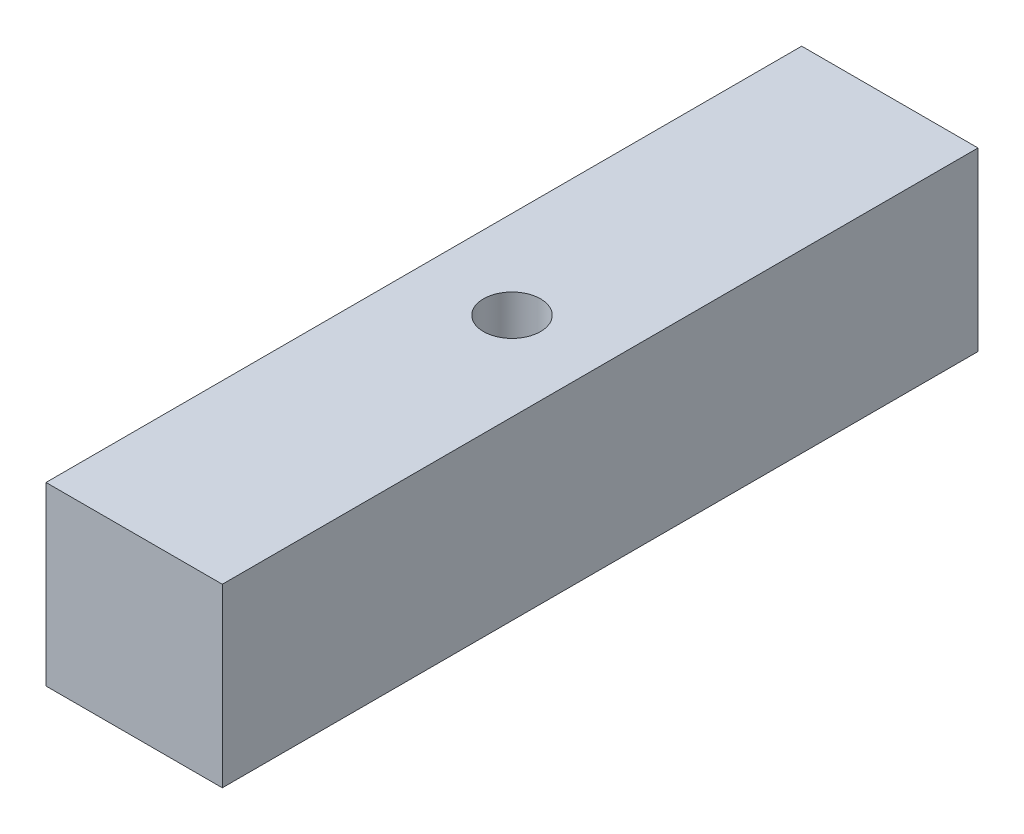
SolidWorks part; units mm, degrees
ref_plane "Front Plane" through (0, 0, 0) normal (0, 0, 1) x (1, 0, 0)
ref_plane "Top Plane" through (0, 0, 0) normal (0, 1, 0) x (1, 0, 0)
ref_plane "Right Plane" through (0, 0, 0) normal (1, 0, 0) x (0, 0, -1)
sketch "Sketch1" plane through (0, 0, 0) normal (0, 0, 1) x (1, 0, 0)
  line L1 (0, 0) -> (7, 0)
  line L2 (0, 0) -> (0, 7)
  line L3 (0, 7) -> (7, 7)
  line L4 (7, 0) -> (7, 7)
  dimension "D1" = 7
  dimension "D2" = 7
extrude "Boss-Extrude1" add sketch "Sketch1" along normal blind 30
sketch "Sketch4" plane through (0, 7, 0) normal (0, 1, 0) x (1, 0, 0)
  line L0 (0, -30) -> (0, 0) construction
  line L1 (7, 0) -> (0, 0) construction
  circle A0 centre (3.5, -15) radius 1.1303
  point P5 (0, -15)
  point P9 (3.5, 0)
  dimension "D1" = 2.2606
extrude "Cut-Extrude3" cut sketch "Sketch4" against normal through all
cosmetic thread "Cosmetic Thread1" parameters "D1"=5, "D2"=2.8448
